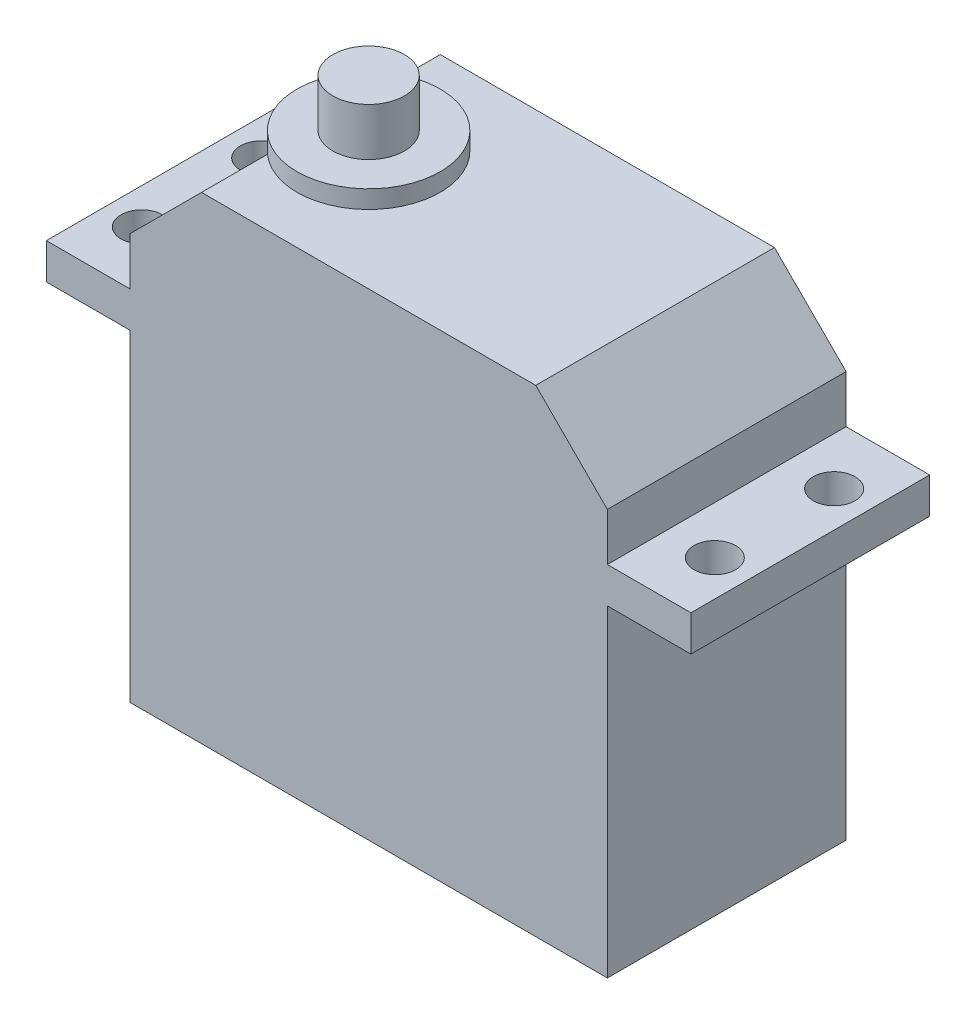
SolidWorks part; units mm, degrees
ref_plane "前视基准面" through (0, 0, 0) normal (0, 0, 1) x (1, 0, 0)
ref_plane "上视基准面" through (0, 0, 0) normal (0, 1, 0) x (1, 0, 0)
ref_plane "右视基准面" through (0, 0, 0) normal (1, 0, 0) x (0, 0, -1)
other "Configuration Table"
sketch "草图1" plane through (0, 0, 0) normal (0, 0, 1) x (1, 0, 0)
  line L1 (0, 0) -> (40, 0)
  line L2 (0, 0) -> (0, 40)
  line L3 (0, 40) -> (40, 40)
  line L4 (40, 0) -> (40, 40)
  dimension "D1" = 40
  dimension "D2" = 40
extrude "凸台-拉伸1" add sketch "草图1" along normal mid plane 20
sketch "草图2" plane through (0, 0, 0) normal (0, 0, 1) x (1, 0, 0)
  line L0 (0, 0) -> (40, 0) construction
  line L1 (-7, 30) -> (47, 30)
  line L2 (-7, 30) -> (-7, 27)
  line L3 (-7, 27) -> (47, 27)
  line L4 (47, 30) -> (47, 27)
  line L5 (40, 40) -> (0, 40) construction
  point P8 (20, 40)
  point P9 (20, 30)
  dimension "D1" = 27
  dimension "D2" = 3
  dimension "D3" = 54
extrude "凸台-拉伸2" add sketch "草图2" along normal mid plane 20
chamfer "倒角1" distance 6 angle 45 2 edges at (40, 40, 0) (0, 40, 0)
sketch "草图4" plane through (0, 40, 0) normal (0, 1, 0) x (1, 0, 0)
  line L0 (34, 10) -> (6, 10) construction
  circle A0 centre (10, 0) radius 6
  point P4 (20, 10)
  dimension "D1" = 12
  dimension "D2" = 10
extrude "凸台-拉伸3" add sketch "草图4" along normal blind 1.5 and the other way blind 20
sketch "草图5" plane through (0, 41.5, 0) normal (0, 1, 0) x (1, 0, 0)
  circle A0 centre (10, 0) radius 3
  dimension "D1" = 6
extrude "凸台-拉伸4" add sketch "草图5" along normal blind 4
sketch "草图6" plane through (0, 30, 0) normal (0, 1, 0) x (1, 0, 0)
  line L0 (34, 10) -> (6, 10) construction
  circle A0 centre (-4, 5) radius 1.75
  circle A1 centre (-4, -5) radius 1.75
  circle A2 centre (44, 5) radius 1.75
  circle A3 centre (44, -5) radius 1.75
  point P15 (20, 10)
  dimension "D1" = 3.5
  dimension "D2" = 10
  dimension "D3" = 5
  dimension "D4" = 48
  dimension "D5" = 24
extrude "切除-拉伸1" cut sketch "草图6" against normal through all
